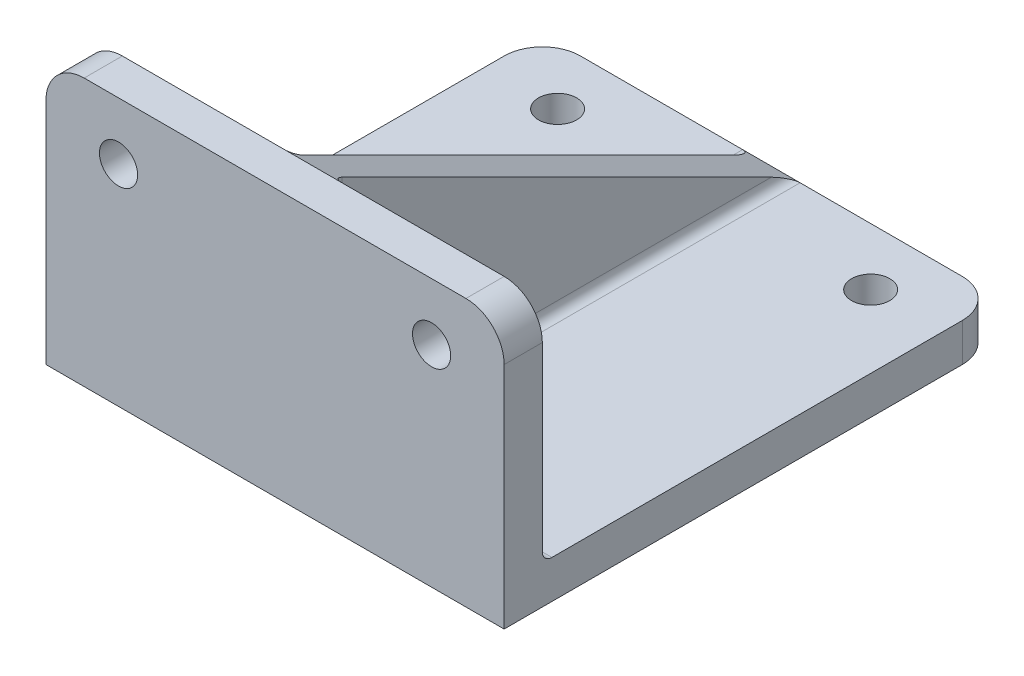
SolidWorks part; units mm, degrees
ref_plane "Front Plane" through (0, 0, 0) normal (0, 0, 1) x (1, 0, 0)
ref_plane "Top Plane" through (0, 0, 0) normal (0, 1, 0) x (1, 0, 0)
ref_plane "Right Plane" through (0, 0, 0) normal (1, 0, 0) x (0, 0, -1)
sketch "Sketch1" plane through (0, 0, 0) normal (1, 0, 0) x (0, 0, -1)
  line L0 (76.2, 0) -> (0, 0)
  line L1 (0, 0) -> (0, 38.1)
  dimension "D1" = 38.1
  dimension "D2" = 76.2
extrude "Extrude-Thin1" add sketch "Sketch1" along normal blind 76.2 thin thin type one direction reverse wall 6.35
fillet "Fillet1" radius 6.35 4 edges at (0, -3.175, -76.2) (76.2, -3.175, -76.2) (0, 38.1, 3.175) (76.2, 38.1, 3.175)
sketch "Sketch2" plane through (0, 0, 0) normal (0, 0, 1) x (1, 0, 0)
  line L0 (38.1, 38.1) -> (38.1, 14.1176) construction
  line L1 (69.85, 38.1) -> (6.35, 38.1) construction
  circle A0 centre (12.065, 28.575) radius 3.175
  circle A1 centre (64.135, 28.575) radius 3.175
  dimension "D1" = 28.575
  dimension "D2" = 12.065
extrude "Cut-Extrude1" cut sketch "Sketch2" along normal blind 76.2
sketch "Sketch3" plane through (0, 0, 0) normal (0, 1, 0) x (1, 0, 0)
  line L0 (38.1, 76.2) -> (38.1, 69.3298) construction
  line L1 (69.85, 76.2) -> (6.35, 76.2) construction
  circle A0 centre (12.065, 66.675) radius 3.175
  circle A1 centre (64.135, 66.675) radius 3.175
  dimension "D1" = 6.35
  dimension "D2" = 66.675
  dimension "D3" = 12.065
extrude "Cut-Extrude2" cut sketch "Sketch3" against normal through all
ref_plane "Plane1" through (0, 30.48, -15.24) normal (0, -0.8944, 0.4472) x (1, 0, 0)
sketch "Sketch4" plane through (0, 30.48, -15.24) normal (0, -0.8944, 0.4472) x (1, 0, 0)
  line L0 (38.1, -68.1554) -> (38.1, 17.0388) construction
  line L1 (69.85, -68.1554) -> (6.35, -68.1554) construction
  line L2 (69.85, 17.0388) -> (6.35, 17.0388) construction
  line L4 (34.925, -68.1554) -> (41.275, -68.1554)
  line L5 (34.925, -68.1554) -> (34.925, 17.0388)
  line L6 (34.925, 17.0388) -> (41.275, 17.0388)
  line L7 (41.275, -68.1554) -> (41.275, 17.0388)
  line L8 (34.925, -68.1554) -> (41.275, 17.0388) construction
  line L9 (34.925, 17.0388) -> (41.275, -68.1554) construction
  point P6 (38.1, -25.5583)
  dimension "D1" = 6.35
extrude "Boss-Extrude1" add sketch "Sketch4" along normal up to next
fillet "Fillet2" radius 1.6002 6 edges at (58.7375, 0, 0) (41.275, 0, -38.1) (41.275, 19.05, 0) (17.4625, 0, 0) (34.925, 0, -38.1) (34.925, 19.05, 0)
